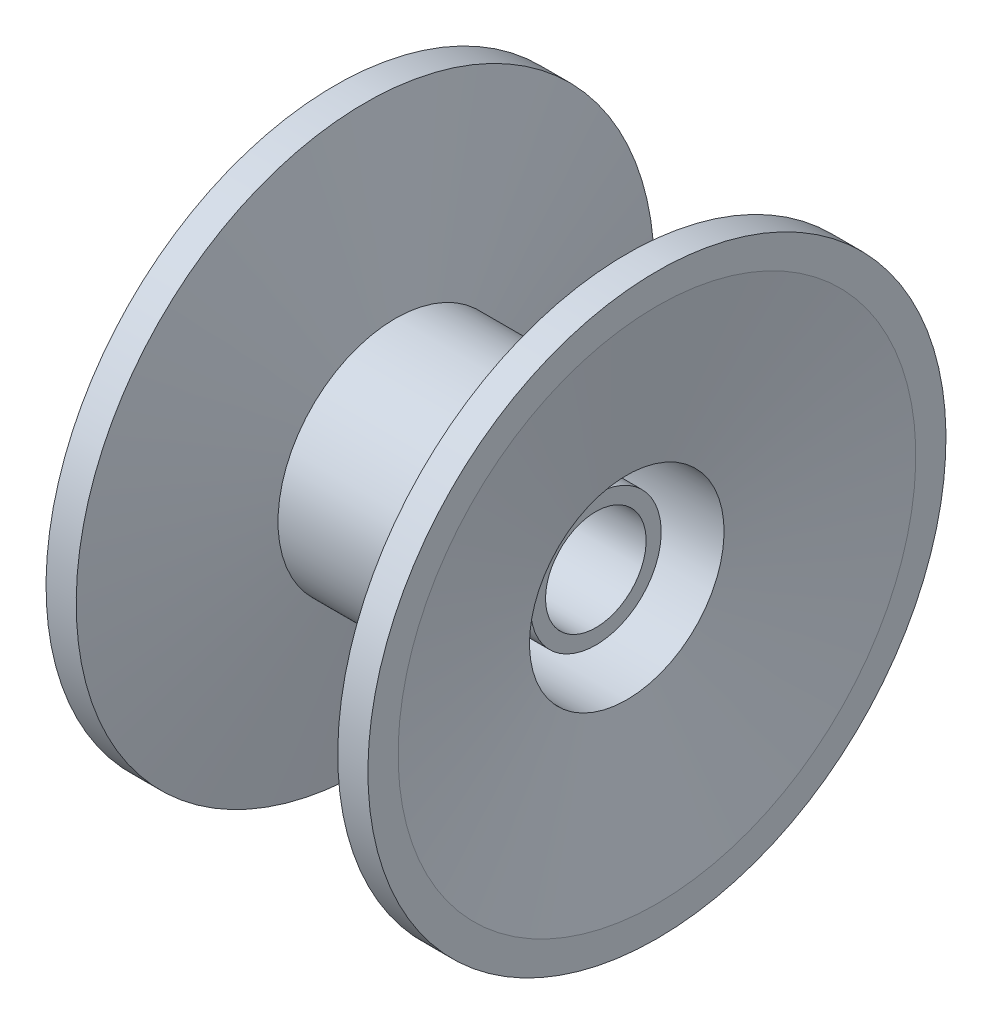
SolidWorks part; units mm, degrees
ref_plane "Front Plane" through (0, 0, 0) normal (0, 0, 1) x (1, 0, 0)
ref_plane "Top Plane" through (0, 0, 0) normal (0, 1, 0) x (1, 0, 0)
ref_plane "Right Plane" through (0, 0, 0) normal (1, 0, 0) x (0, 0, -1)
sketch "Sketch1" plane through (0, 0, 0) normal (0, 0, 1) x (1, 0, 0)
  line L0 (-8, 14.3666) -> (-6.5, 14.3666)
  line L1 (-6.5, 14.3666) -> (-5, 5.8362)
  line L2 (-5, 5.8362) -> (5, 5.8362)
  line L3 (-8, 14.3666) -> (-8, 12.8666)
  line L4 (-8, 12.8666) -> (-6.5, 4.8362)
  line L5 (-6.5, 4.8362) -> (6.5, 4.8362)
  line L6 (0, 5.8362) -> (0, 0) construction
  line L7 (8, 12.8666) -> (6.5, 4.8362)
  line L8 (8, 14.3666) -> (8, 12.8666)
  line L9 (6.5, 14.3666) -> (5, 5.8362)
  line L10 (8, 14.3666) -> (6.5, 14.3666)
  line L11 (-5, 0) -> (5, 0)
  point P8 (0, 4.8362)
  point P15 (0, 0)
  point P16 (0, 0)
  dimension "D1" = 1.5
  dimension "D2" = 1.5
  dimension "D3" = 5
  dimension "D4" = 6.5
  dimension "D5" = 1
  dimension "D6" = 10
  dimension "D7" = 3
revolve "Revolve1" add sketch "Sketch1" angle 360 about L11
sketch "Sketch2" plane through (0, 0, 0) normal (0, 0, 1) x (1, 0, 0)
  line L0 (-7.25, 8.8514) -> (-7.1123, 8.1141)
  line L1 (-8, 12.8666) -> (-6.5, 4.8362) construction
  line L2 (-6.2881, 3.25) -> (4.9619, 3.25)
  line L3 (-6.2881, 3.25) -> (-6.2881, 4.4188)
  line L4 (0, 5.8362) -> (0, 0) construction
  line L5 (-7.0381, 2.5) -> (-5.5381, 2.5)
  line L6 (-5, 0) -> (5, 0) construction
  line L7 (-7.0381, 2.5) -> (-7.6023, 4.4188)
  line L8 (-5.5381, 2.5) -> (-5.5381, 0)
  line L9 (-5.5381, 0) -> (-4.7881, 0)
  line L10 (-4.7881, 0) -> (-4.7881, 2.5)
  line L11 (-4.7881, 2.5) -> (4.9619, 2.5)
  line L12 (4.9619, 3.25) -> (4.9619, 2.5)
  arc A0 (-7.25, 8.8514) -> (-7.6023, 4.4188) centre (5.474, 5.6097) ccw
  arc A1 (-7.1123, 8.1141) -> (-6.2881, 4.4188) centre (6.1357, 9.1293) ccw
  point P12 (0, -3.7874)
  dimension "D1" = 0.75
  dimension "D2" = 11.25
  dimension "D3" = 12
  dimension "D4" = 0.75
  dimension "D5" = 2.5
  dimension "D6" = 2
  dimension "D8" = 0.75
  dimension "D9" = 1.5
  dimension "D10" = 1.25
revolve "Revolve2" add sketch "Sketch2" angle 360 about L9
